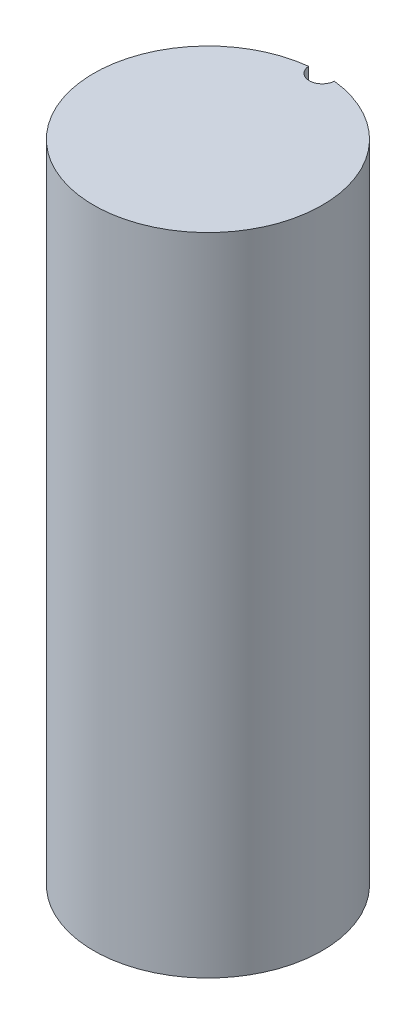
SolidWorks part; units mm, degrees
ref_plane "Front Plane" through (0, 0, 0) normal (0, 0, 1) x (1, 0, 0)
ref_plane "Top Plane" through (0, 0, 0) normal (0, 1, 0) x (1, 0, 0)
ref_plane "Right Plane" through (0, 0, 0) normal (1, 0, 0) x (0, 0, -1)
sketch "Sketch1" plane through (0, 0, 0) normal (0, 1, 0) x (1, 0, 0)
  circle A0 centre (0, 0) radius 8.9916
  dimension "D1" = 17.9832
extrude "Boss-Extrude1" add sketch "Sketch1" along normal blind 50.8
sketch "Sketch2" plane through (0, 50.8, 0) normal (0, 1, 0) x (1, 0, 0)
  circle A0 centre (0, 8.9916) radius 1.016
  circle A1 centre (0, 0) radius 8.9916 construction
  dimension "D1" = 2.032
extrude "Cut-Extrude1" cut sketch "Sketch2" against normal through all
